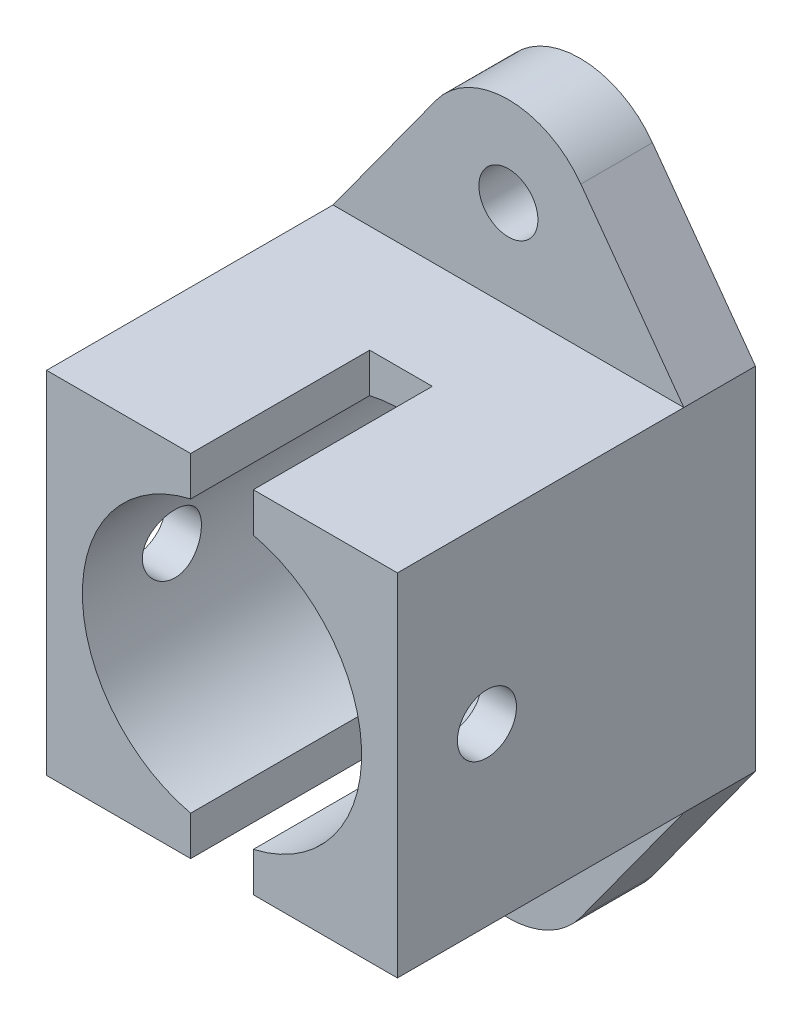
SolidWorks part; units mm, degrees
material "POM 乙缩醛共聚物"
ref_plane "前视基准面" through (0, 0, 0) normal (0, 0, 1) x (1, 0, 0)
ref_plane "上视基准面" through (0, 0, 0) normal (0, 1, 0) x (1, 0, 0)
ref_plane "右视基准面" through (0, 0, 0) normal (1, 0, 0) x (0, 0, -1)
sketch "草图1" plane through (0, 0, 0) normal (0, 0, 1) x (1, 0, 0)
  line L9 (-9.8, -9.8) -> (9.8, -9.8)
  line L10 (-9.8, -9.8) -> (-9.8, 9.8)
  line L11 (-9.8, 9.8) -> (9.8, 9.8)
  line L12 (9.8, -9.8) -> (9.8, 9.8)
  line L13 (-9.8, -9.8) -> (9.8, 9.8) construction
  line L14 (-9.8, 9.8) -> (9.8, -9.8) construction
  circle A3 centre (0, 0) radius 7.8
  point P0 (0, 0)
  dimension "D1" = 19.6
  dimension "D2" = 15.6
extrude "凸台-拉伸1" add sketch "草图1" along normal blind 20
sketch "草图2" plane through (0, 0, 0) normal (0, 0, -1) x (-1, 0, 0)
  line L0 (-9.8, 9.8) -> (-4.0482, 17.7346)
  line L1 (4.0482, 17.7346) -> (9.8, 9.8)
  line L2 (0, 9.8) -> (0, 21.084) construction
  line L3 (-9.8, 9.8) -> (9.8, 9.8) construction
  line L4 (-9.8, 9.8) -> (9.8, 9.8)
  line L5 (-9.8, 0) -> (9.8, 0) construction
  line L6 (-9.8, -9.8) -> (-9.8, 9.8) construction
  line L7 (9.8, 9.8) -> (9.8, -9.8) construction
  line L8 (-9.8, -9.8) -> (9.8, -9.8)
  line L9 (4.0482, -17.7346) -> (9.8, -9.8)
  line L10 (-9.8, -9.8) -> (-4.0482, -17.7346)
  arc A0 (-4.0482, 17.7346) -> (4.0482, 17.7346) centre (0, 14.8) cw
  circle A1 centre (0, 14.8) radius 1.65
  circle A2 centre (0, -14.8) radius 1.65
  arc A3 (-4.0482, -17.7346) -> (4.0482, -17.7346) centre (0, -14.8) ccw
  dimension "D1" = 3.3
  dimension "D2" = 5
  dimension "D3" = 5
extrude "凸台-拉伸2" add sketch "草图2" against normal blind 4
sketch "草图3" plane through (9.8, 0, 0) normal (1, 0, 0) x (0, 0, -1)
  line L0 (0, 0) -> (-20, 0) construction
  line L1 (-20, -9.8) -> (-20, 9.8) construction
  circle A0 centre (-15, 0) radius 1.65
  dimension "D1" = 3.3
  dimension "D2" = 5
extrude "切除-拉伸1" cut sketch "草图3" against normal through all
sketch "草图4" plane through (0, 0, 20) normal (0, 0, 1) x (1, 0, 0)
  line L0 (9.8, 9.8) -> (-9.8, 9.8) construction
  line L1 (-1.75, 9.8) -> (1.75, 9.8)
  line L2 (-1.75, 9.8) -> (-1.75, -9.8)
  line L3 (-1.75, -9.8) -> (1.75, -9.8)
  line L4 (1.75, 9.8) -> (1.75, -9.8)
  line L5 (-9.8, -9.8) -> (9.8, -9.8) construction
  line L6 (0, -9.8) -> (0, 9.8) construction
  dimension "D1" = 3.5
extrude "切除-拉伸2" cut sketch "草图4" against normal blind 10
